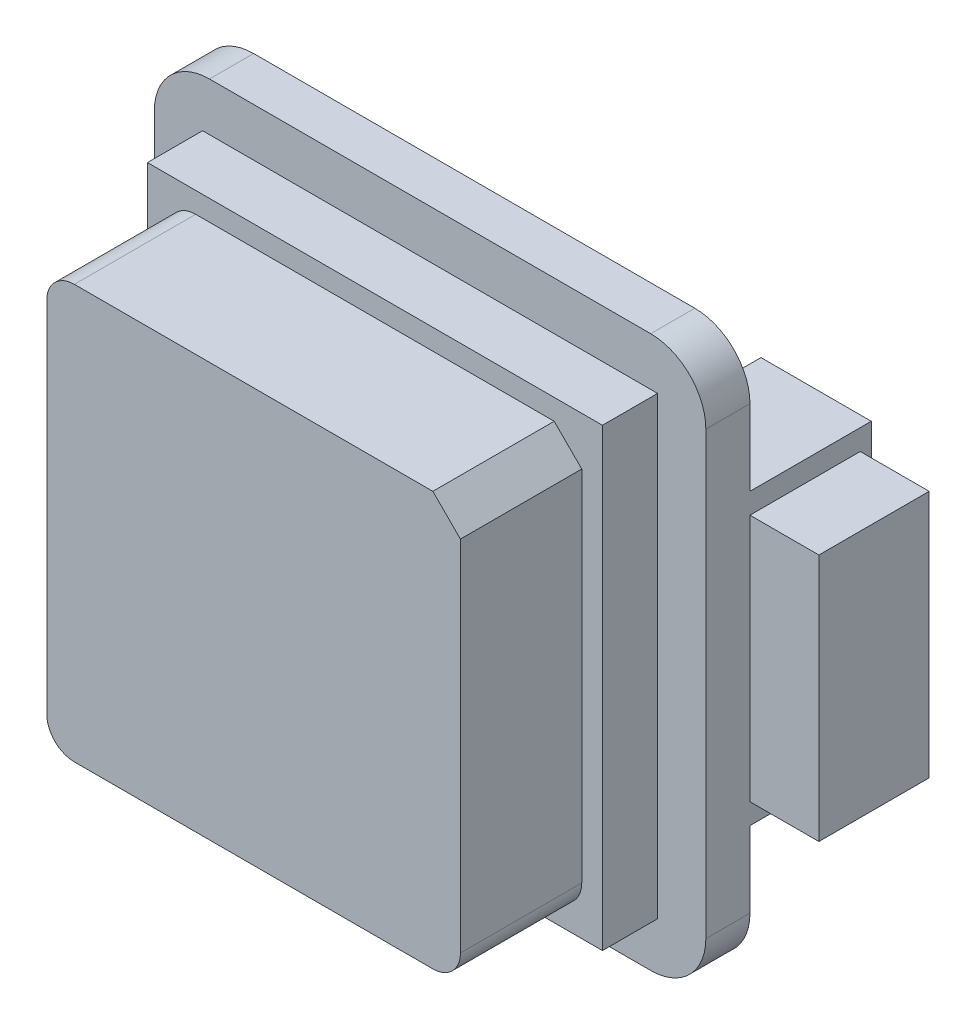
SolidWorks part; units mm, degrees
ref_plane "Front Plane" through (0, 0, 0) normal (1, 0, 0) x (0, 1, 0)
ref_plane "Top Plane" through (0, 0, 0) normal (0, 0, 1) x (0, 1, 0)
ref_plane "Right Plane" through (0, 0, 0) normal (0, 1, 0) x (-1, 0, 0)
sketch "Sketch1" plane through (0, 0, 0) normal (0, 0, 1) x (0, 1, 0)
  line L1 (-8, 10) -> (8, 10)
  line L2 (-10, 8) -> (-10, -8)
  line L3 (-8, -10) -> (8, -10)
  line L4 (10, 8) -> (10, -8)
  line L5 (-10, 10) -> (10, -10) construction
  line L6 (-10, -10) -> (10, 10) construction
  arc A0 (8, -10) -> (10, -8) centre (8, -8) ccw
  arc A1 (-10, -8) -> (-8, -10) centre (-8, -8) ccw
  arc A2 (-8, 10) -> (-10, 8) centre (-8, 8) ccw
  arc A3 (8, 10) -> (10, 8) centre (8, 8) cw
  point P0 (0, 0)
  dimension "D2" = 2
  dimension "D1" = 20
extrude "Boss-Extrude1" add sketch "Sketch1" along normal blind 1.6
sketch "Sketch2" plane through (0, 0, 1.6) normal (0, 0, 1) x (1, 0, 0)
  line L1 (-8.25, 8.25) -> (8.25, 8.25)
  line L2 (-8.25, 8.25) -> (-8.25, -8.25)
  line L3 (-8.25, -8.25) -> (8.25, -8.25)
  line L4 (8.25, 8.25) -> (8.25, -8.25)
  line L5 (-8.25, 8.25) -> (8.25, -8.25) construction
  line L6 (-8.25, -8.25) -> (8.25, 8.25) construction
  point P0 (0, 0)
  dimension "D1" = 16.5
extrude "Boss-Extrude2" add sketch "Sketch2" along normal blind 2
sketch "Sketch3" plane through (0, 0, 3.6) normal (0, 0, 1) x (1, 0, 0)
  line L0 (6.5, 7.5) -> (7.5, 6.5)
  line L1 (-6.5, 7.5) -> (6.5, 7.5)
  line L2 (-7.5, 6.5) -> (-7.5, -6.5)
  line L3 (-6.5, -7.5) -> (6.5, -7.5)
  line L4 (7.5, 6.5) -> (7.5, -6.5)
  line L5 (-7.5, 7.5) -> (7.5, -7.5) construction
  line L6 (-7.5, -7.5) -> (7.5, 7.5) construction
  arc A0 (6.5, -7.5) -> (7.5, -6.5) centre (6.5, -6.5) ccw
  arc A1 (-7.5, -6.5) -> (-6.5, -7.5) centre (-6.5, -6.5) ccw
  arc A2 (-6.5, 7.5) -> (-7.5, 6.5) centre (-6.5, 6.5) ccw
  point P0 (0, 0)
  point P17 (6.5, 7.4195)
  dimension "D2" = 1
  dimension "D1" = 15
extrude "Boss-Extrude3" add sketch "Sketch3" along normal offset from surface (4.4 mm away) 8 up to face at (0, 0, 0)
sketch "Sketch5" plane through (0, 0, 0) normal (0, 0, -1) x (1, 0, 0)
  line L0 (-10, -8) -> (-10, 8) construction
  line L1 (-10, 5.25) -> (-6, 5.25)
  line L2 (-10, 5.25) -> (-10, -5.25)
  line L3 (-10, -5.25) -> (-6, -5.25)
  line L4 (-6, 5.25) -> (-6, -5.25)
  line L5 (10, 8) -> (10, -8) construction
  line L6 (10, 5.25) -> (6, 5.25)
  line L7 (10, 5.25) -> (10, -5.25)
  line L8 (10, -5.25) -> (6, -5.25)
  line L9 (6, 5.25) -> (6, -5.25)
  point P6 (-6, 0)
  point P15 (0, 0)
  dimension "D1" = 4
  dimension "D2" = 10.5
extrude "Boss-Extrude4" add sketch "Sketch5" along normal blind 4.4
sketch "Sketch6" plane through (10, 0, 0) normal (-1, 0, 0) x (0, -1, 0)
  line L0 (-8, 0) -> (-5.25, 0) construction
  line L1 (-4.5, 0) -> (4.5, 0)
  line L2 (-4.5, 0) -> (-4.5, -4)
  line L3 (-4.5, -4) -> (4.5, -4)
  line L4 (4.5, 0) -> (4.5, -4)
  line L5 (-4.5, 0) -> (4.5, -4) construction
  line L6 (-4.5, -4) -> (4.5, 0) construction
  point P0 (0, -2)
  point P5 (0, 0)
  point P6 (0, -2.3019)
  point P7 (0, -2.1277)
  point P10 (0, 0)
  dimension "D1" = 4
  dimension "D2" = 9
extrude "Boss-Extrude5" add sketch "Sketch6" against normal offset from surface (2.5 mm away) 22.5 up to face at (-10, 0, -0.7)
